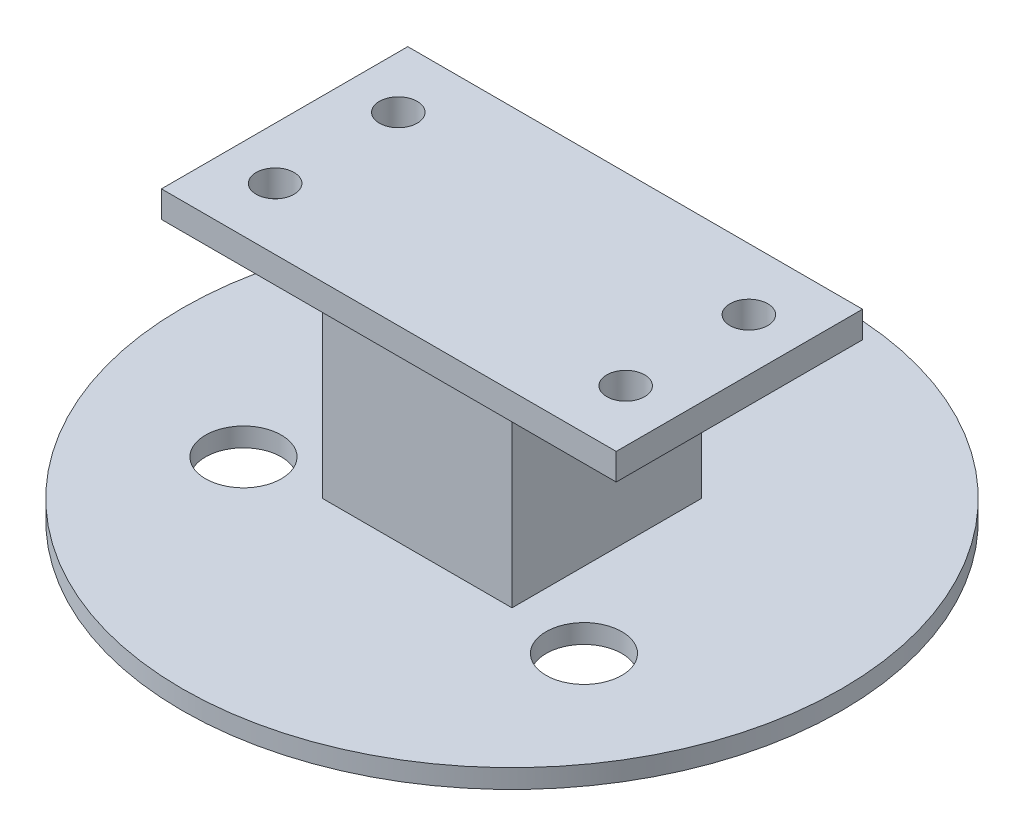
SolidWorks part; units mm, degrees
ref_plane "Front Plane" through (0, 0, 0) normal (0, 0, 1) x (1, 0, 0)
ref_plane "Top Plane" through (0, 0, 0) normal (0, 1, 0) x (1, 0, 0)
ref_plane "Right Plane" through (0, 0, 0) normal (1, 0, 0) x (0, 0, -1)
sketch "Sketch1" plane through (0, 0, 0) normal (0, 1, 0) x (1, 0, 0)
  circle A0 centre (0, 0) radius 51.875 construction
  circle A2 centre (0, 51.875) radius 10
  circle A3 centre (44.9266, -25.9366) radius 10
  circle A4 centre (-44.9236, -25.9384) radius 10
  circle A5 centre (0, 0) radius 87
  point P12 (0.001, 0)
extrude "Boss-Extrude1" add sketch "Sketch1" along normal blind 5
sketch "Sketch2" plane through (0, 5, 0) normal (0, 1, 0) x (1, 0, 0)
  line L1 (-25, 25) -> (25, 25)
  line L2 (-25, 25) -> (-25, -25)
  line L3 (-25, -25) -> (25, -25)
  line L4 (25, 25) -> (25, -25)
  line L5 (-25, 25) -> (25, -25) construction
  line L6 (-25, -25) -> (25, 25) construction
  point P0 (0, 0)
  dimension "D1" = 50
  dimension "D2" = 50
extrude "Boss-Extrude2" add sketch "Sketch2" along normal blind 50
sketch "Sketch3" plane through (0, 55, 0) normal (0, 1, 0) x (1, 0, 0)
  line L0 (-60, 0) -> (0, 0) construction
  line L1 (-60, 32.5) -> (60, 32.5)
  line L2 (-60, 32.5) -> (-60, -32.5)
  line L3 (-60, -32.5) -> (60, -32.5)
  line L4 (60, 32.5) -> (60, -32.5)
  line L5 (-60, 32.5) -> (60, -32.5) construction
  line L6 (-60, -32.5) -> (60, 32.5) construction
  line L7 (0, 0) -> (0, 32.5) construction
  line L8 (-32.5, 32.5) -> (-32.5, 17.6042) construction
  line L9 (-32.5, 0) -> (-32.5, -32.5) construction
  line L10 (-32.5, -16.25) -> (-60, -16.25) construction
  circle A1 centre (-46.25, -16.25) radius 5
  circle A2 centre (-46.25, 16.25) radius 5
  circle A3 centre (46.25, -16.25) radius 5
  circle A4 centre (46.25, 16.25) radius 5
  point P0 (0, 0)
  dimension "D1" = 120
  dimension "D2" = 65
  dimension "D3" = 27.5
extrude "Boss-Extrude3" add sketch "Sketch3" along normal blind 7
